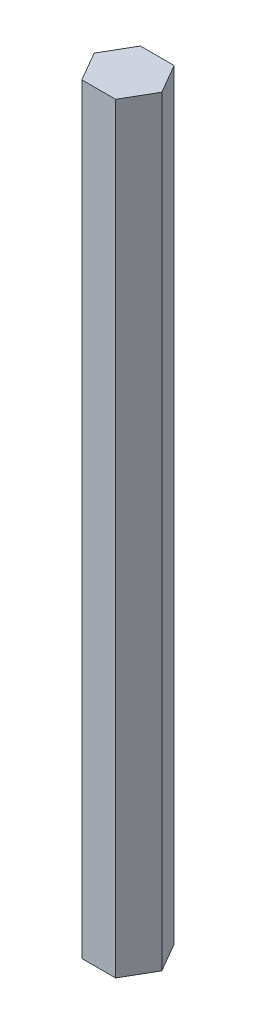
SolidWorks part; units mm, degrees
ref_plane "Front Plane" through (0, 0, 0) normal (0, 0, 1) x (1, 0, 0)
ref_plane "Top Plane" through (0, 0, 0) normal (0, 1, 0) x (1, 0, 0)
ref_plane "Right Plane" through (0, 0, 0) normal (1, 0, 0) x (0, 0, -1)
sketch "Sketch1" plane through (0, 0, 0) normal (0, 1, 0) x (1, 0, 0)
  line L1 (7.3323, 0) -> (3.6662, 6.35)
  line L2 (3.6662, 6.35) -> (-3.6662, 6.35)
  line L3 (-3.6662, 6.35) -> (-7.3323, 0)
  line L4 (-7.3323, 0) -> (-3.6662, -6.35)
  line L5 (-3.6662, -6.35) -> (3.6662, -6.35)
  line L6 (3.6662, -6.35) -> (7.3323, 0)
  circle A0 centre (0, 0) radius 6.35 construction
extrude "Boss-Extrude1" add sketch "Sketch1" along normal blind 165.1 contours L2 L3 L4 L5 L6 L1
